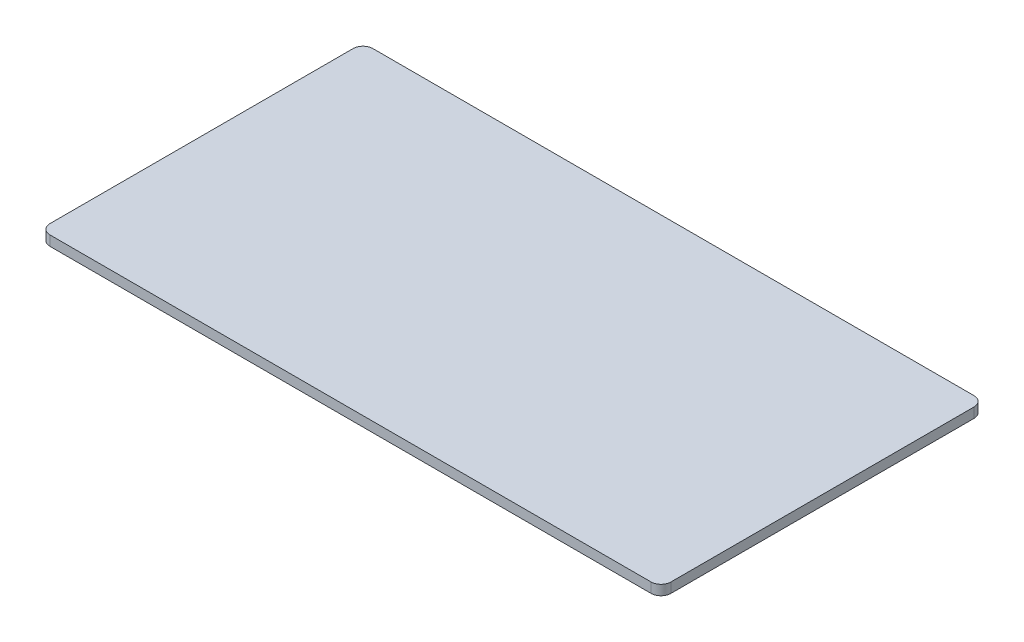
SolidWorks part; units mm, degrees
ref_plane "Front Plane" through (0, 0, 0) normal (0, 0, 1) x (1, 0, 0)
ref_plane "Top Plane" through (0, 0, 0) normal (0, 1, 0) x (1, 0, 0)
ref_plane "Right Plane" through (0, 0, 0) normal (1, 0, 0) x (0, 0, -1)
sketch "Sketch2" plane through (0, 0, 0) normal (0, 1, 0) x (1, 0, 0)
  line L0 (0, 0) -> (0, 82.55)
  line L1 (0, 0) -> (158.75, 0)
  line L2 (158.75, 0) -> (158.75, 82.55)
  line L3 (0, 82.55) -> (158.75, 82.55)
  point P4 (0, 0)
extrude "Boss-Extrude1" add sketch "Sketch2" along normal blind 2.54
fillet "Fillet1" radius 2.54 4 edges at (0, 1.27, 0) (158.75, 1.27, 0) (158.75, 1.27, -82.55) (0, 1.27, -82.55)
